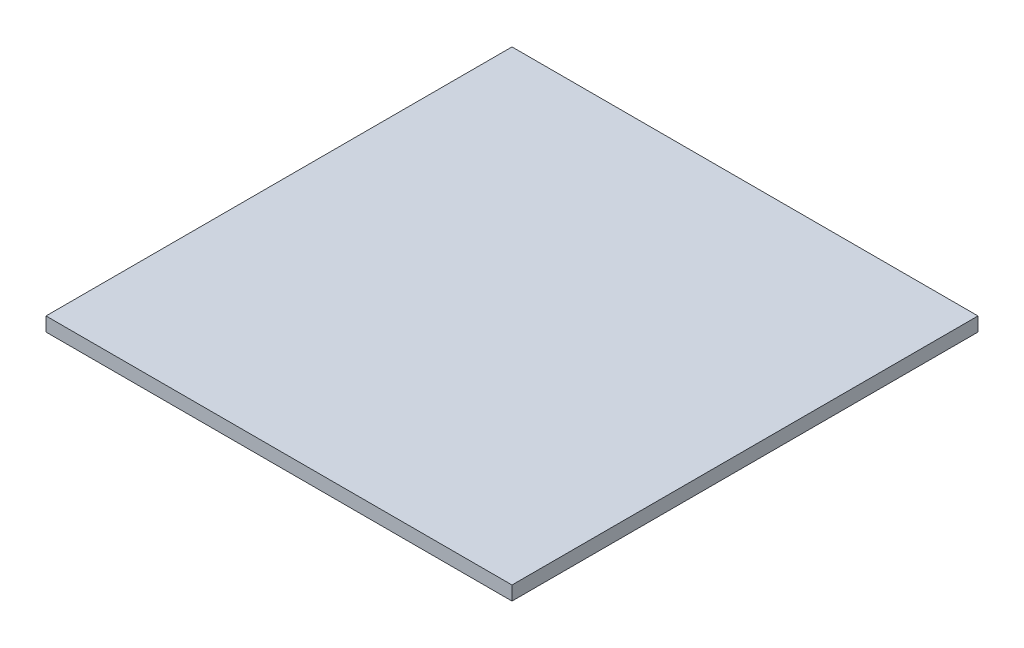
SolidWorks part; units mm, degrees
ref_plane "Front Plane" through (0, 0, 0) normal (0, 0, 1) x (1, 0, 0)
ref_plane "Top Plane" through (0, 0, 0) normal (0, 1, 0) x (1, 0, 0)
ref_plane "Right Plane" through (0, 0, 0) normal (1, 0, 0) x (0, 0, -1)
sketch "Sketch1" plane through (0, 0, 0) normal (0, 1, 0) x (1, 0, 0)
  line L1 (0, 0) -> (10, 0)
  line L2 (0, 0) -> (0, 10)
  line L3 (0, 10) -> (10, 10)
  line L4 (10, 0) -> (10, 10)
  dimension "D1" = 10
  dimension "D2" = 10
extrude "Boss-Extrude1" add sketch "Sketch1" along normal blind 0.3
